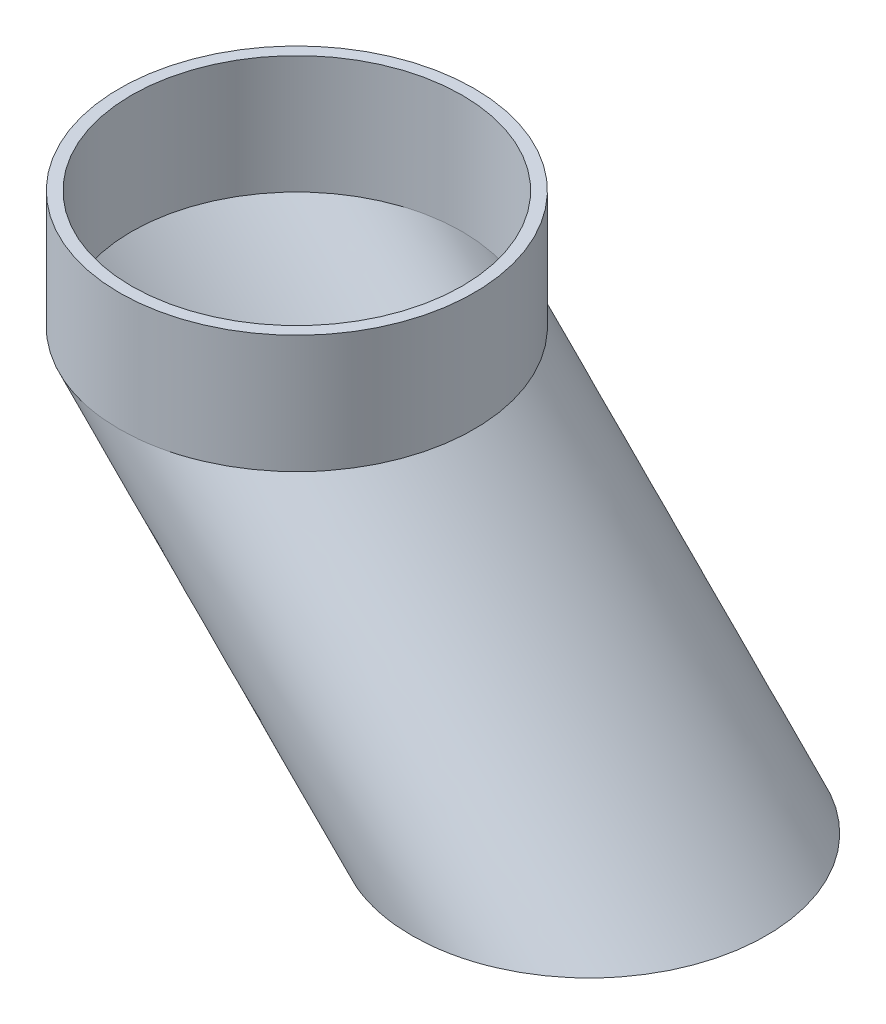
SolidWorks part; units mm, degrees
ref_plane "Front Plane" through (0, 0, 0) normal (0, 0, 1) x (1, 0, 0)
ref_plane "Top Plane" through (0, 0, 0) normal (0, 1, 0) x (1, 0, 0)
ref_plane "Right Plane" through (0, 0, 0) normal (1, 0, 0) x (0, 0, -1)
sketch "Sketch1" plane through (0, 0, 0) normal (0, 1, 0) x (1, 0, 0)
  circle A0 centre (0, 0) radius 15
  dimension "D1" = 30
extrude "Extrude-Thin1" add sketch "Sketch1" along normal blind 10 thin thin type one direction reverse wall 1
sketch "Sketch2" plane through (0, 0, 0) normal (0, -1, 0) x (1, 0, 0)
  circle A0 centre (0, 0) radius 15
  circle A1 centre (0, 0) radius 14
  dimension "D1" = 28
  dimension "D2" = 30
sketch "Sketch4" plane through (0, 0, 0) normal (0, 0, 1) x (1, 0, 0)
  line L0 (0, 0) -> (24.7487, -24.7487)
  line L1 (0, 0) -> (0, -35.0268) construction
  dimension "D1" = 35
  dimension "D2" = 45
sweep "Sweep1" add profiles "Sketch2" path "Sketch4"
